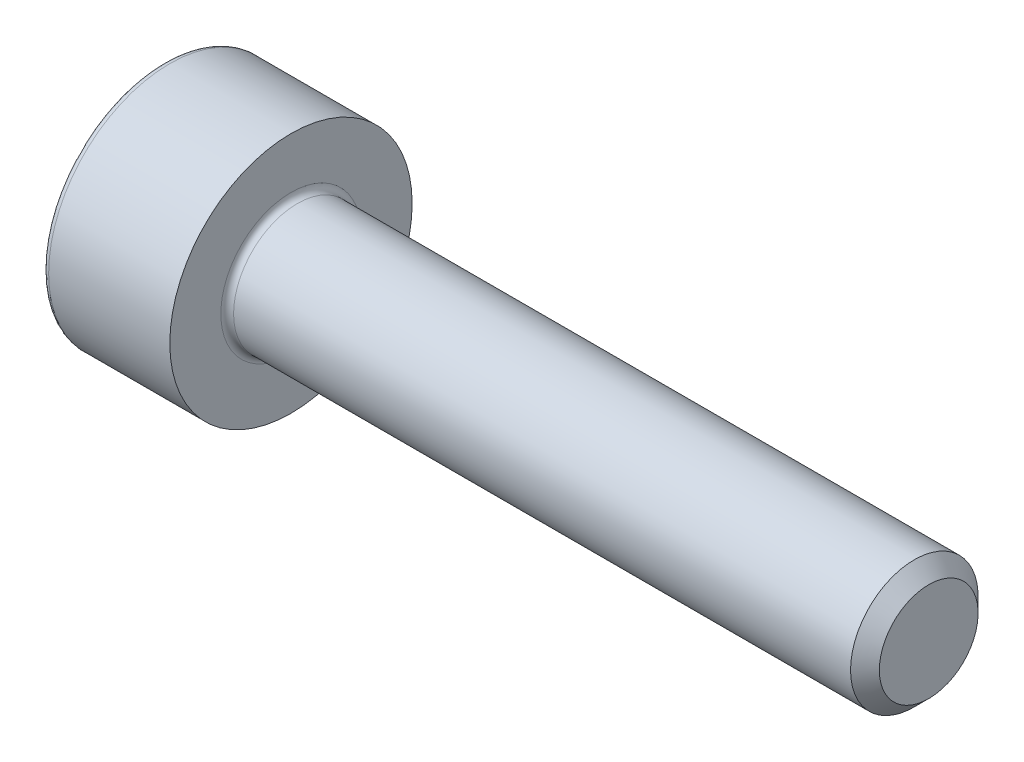
SolidWorks part; units mm, degrees
revolve "Base-Revolve" add sketch "BodySke"
sketch "BodySke" plane through (0, 0, 0) normal (0, 0, 1) x (1, 0, 0)
  line L0 (0, 0) -> (0, 1.9)
  line L1 (0, 1.9) -> (2, 1.9)
  line L2 (2, 1.9) -> (2, 1)
  line L3 (2, 1) -> (11.774, 1)
  line L4 (12, 0.774) -> (12, 0)
  line L5 (12, 0) -> (0, 0)
  line L6 (-31.75, 0) -> (127, 0) construction
  line L8 (12, 0.774) -> (11.774, 1)
  line L10 (12, -0.774) -> (11.774, -1) construction
  line L11 (2.4, 9.525) -> (2.4, 3.175) construction
  line L12 (2, 9.525) -> (2, 3.175) construction
  line L13 (-48, 9.525) -> (-48, 3.175) construction
  dimension "Head_ht" = 2
  dimension "Length" = 10
  dimension "Body_ch_ang" = 45
  dimension "Diameter" = 2
  dimension "Minor_dia" = 1.548
  dimension "Advance" = 0.4
  dimension "Thread_nom" = 10
  dimension "Thread_length" = 60
  dimension "Head_dia" = 3.8
cosmetic thread "ThreadCosmetic" [suppressed]
fillet "Fillet1" radius 0.1 1 edges at (2, 0, 1)
fillet "Fillet2" radius 0.1 1 edges at (0, 0, 1.9)
ref_plane "Plane1" through (0, 0, 0) normal (0, 0, 1) x (1, 0, 0)
ref_plane "Plane2" through (0, 0, 0) normal (0, 1, 0) x (1, 0, 0)
ref_plane "Plane3" through (0, 0, 0) normal (1, 0, 0) x (0, 0, -1)
other "Configuration Table"
sketch "Sketch2" plane through (0, 0, 0) normal (0, 0, 1) x (1, 0, 0)
  line L0 (0, 0.7725) -> (1, 0.7725)
  line L1 (1, 0.7725) -> (1.446, 0)
  line L2 (-31.75, 0) -> (127, 0) construction
  line L3 (1.446, 0) -> (0, 0)
  line L4 (0, 0) -> (0, 0.7725)
  line L6 (0, 0) -> (47.625, 0) construction
  dimension "D1" = 0.7725
  dimension "D2" = 60
  dimension "Depth" = 1
revolve "Hex-PreBroach" cut sketch "Sketch2" angle 360 about L6
sketch "Sketch3" plane through (0, 0, 0) normal (-1, 0, 0) x (0, 0.5, 0.866)
  line L0 (0.446, 0.7725) -> (-0.446, 0.7725)
  line L1 (-0.446, 0.7725) -> (-0.892, 0)
  line L2 (0.446, 0.7725) -> (0.892, 0)
  line L3 (0.446, -0.7725) -> (0.892, 0)
  line L4 (0.446, -0.7725) -> (-0.446, -0.7725)
  line L5 (-0.446, -0.7725) -> (-0.892, 0)
  dimension "D1" = 0.7725
  dimension "D2" = 0.7725
  dimension "Hex_size" = 1.545
extrude "Hex" cut sketch "Sketch3" against normal blind 1
sketch "ThdSchSke" plane through (0, 0, 0) normal (0, 0, 1) x (1, 0, 0)
  line L0 (3.2, -0.774) -> (3.0418, -1)
  line L1 (3.2, -0.774) -> (3.3582, -1)
  line L2 (3.3582, -1) -> (3.3582, -1.25)
  line L3 (-3.175, 0) -> (5.1513, 0) construction
  line L4 (0, 1.8) -> (0, -1.8) construction
  line L5 (3.3582, -1.25) -> (3.0418, -1.25)
  line L6 (3.0418, -1.25) -> (3.0418, -1)
  dimension "Thread_minor" = 1.548
  dimension "Diameter" = 2
  dimension "Start" = 3.2
revolve "ThreadSchematic" [suppressed] cut sketch "ThdSchSke" angle 360 about L3
pattern_linear "ThdSchPat" [suppressed]
equation "\"D2@Sketch3\" = \"Hex_size@Sketch3\" / 2"
equation "\"D1@Sketch3\" = \"Hex_size@Sketch3\" / 2"
equation "\"D1@Sketch2\" = \"Hex_size@Sketch3\" / 2"
equation "\"Thread_minor@ThreadCosmetic\"  =  \"Minor_dia@BodySke\""
equation "\"Depth@Sketch2\" =  \"Key_eng@Hex\""
equation "\"Thread_length@ThreadCosmetic\" = ((sgn( (\"Length@BodySke\" - \"Advance@BodySke\" * 3.0) - \"Thread_nom@BodySke\" )-1)*( (\"Length@BodySke\" - \"Advance@BodySke\" * 3.0) - \"Thread_nom@BodySke\" ))/-2+ \"Thread_nom@BodySke\""
equation "\"Thread_minor@ThdSchSke\" = \"Minor_dia@BodySke\""
equation "\"Diameter@ThdSchSke\" = \"Diameter@BodySke\""
equation "\"Overcut@ThdSchSke\" = \"Diameter@BodySke\" * 1.25"
equation "\"Start@ThdSchSke\" = \"Head_ht@BodySke\" + \"Length@BodySke\" - \"Thread_length@ThreadCosmetic\"  '---Non-countersunk---"
equation "\"Num_threads@ThdSchPat\" = int( \"Thread_length@ThreadCosmetic\" / \"Advance@BodySke\" + 0.999 )  + 1"
equation "\"Advance@ThdSchPat\" = \"Thread_length@ThreadCosmetic\" /  (\"Num_threads@ThdSchPat\" - 1) 'relax it"
equation "\"Num_threads@ThdSchPat\" = \"Num_threads@ThdSchPat\" - sgn( \"Num_threads@ThdSchPat\" - 1) '---chamfered tips only---"
